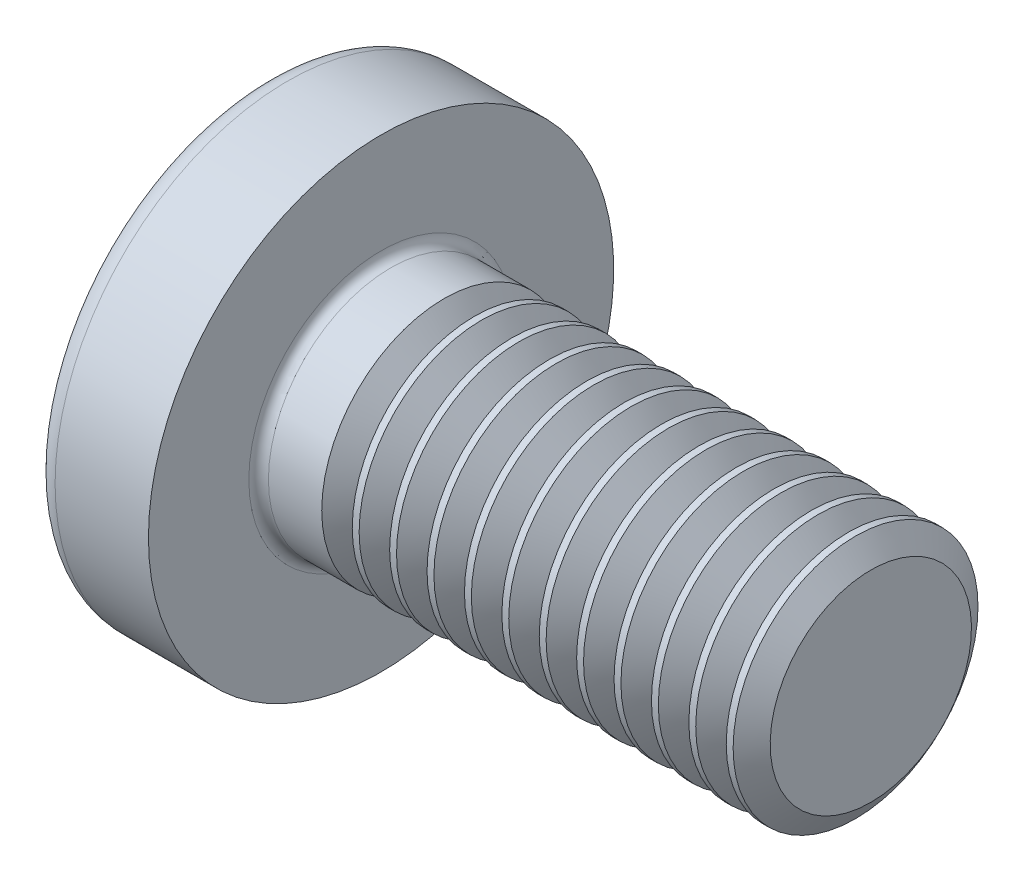
SolidWorks part; units mm, degrees
ref_plane "Plane1" through (0, 0, 0) normal (0, 0, 1) x (1, 0, 0)
ref_plane "Plane2" through (0, 0, 0) normal (0, 1, 0) x (1, 0, 0)
ref_plane "Plane3" through (0, 0, 0) normal (1, 0, 0) x (0, 0, -1)
sketch "BodySke" plane through (0, 0, 0) normal (0, 0, 1) x (1, 0, 0)
  line L0 (3.7, 2.5) -> (3.7, 4.75)
  line L1 (4.1, 6.35) -> (4.1, -3.175) construction
  line L2 (-25.4, 0) -> (127, 0) construction
  line L3 (13.7, 0) -> (0, 0)
  line L4 (3.7, 2.5) -> (13.7, 2.5)
  line L5 (13.7, 2.5) -> (13.7, 0)
  line L6 (1.7942, 4.75) -> (3.7, 4.75)
  line L8 (3.7, 6.35) -> (3.7, -3.175) construction
  arc A0 (1.4243, 4.5563) -> (0, 0) centre (8, 0) ccw
  arc A2 (1.4243, 4.5563) -> (1.7942, 4.75) centre (1.7942, 4.3) cw
  dimension "Head_crown_rad" = 8
  dimension "Head_fillet_rad" = 0.45
  dimension "Length" = 10
  dimension "Head_ht" = 3.7
  dimension "Head_dia" = 9.5
  dimension "Advance" = 0.8
  dimension "Thread_nom" = 10
  dimension "Diameter" = 5
revolve "Base-Revolve" add sketch "BodySke"
cosmetic thread "ThreadCosmetic" [suppressed]
fillet "Fillet1" radius 0.2 1 edges at (3.7, 0, 2.5)
sketch "Sketch3" plane through (0, 0, 0) normal (1, 0, 0) x (0, 0, -1)
  line L0 (0.515, -2.35) -> (-0.515, -2.35)
  line L1 (0.515, -2.35) -> (0.515, 2.35)
  line L2 (-0.515, 2.35) -> (0.515, 2.35)
  line L3 (-0.515, 2.35) -> (-0.515, -2.35)
  dimension "Cross_dia" = 4.7
  dimension "D1" = 2.35
  dimension "Cross_width" = 1.03
  dimension "D2" = 0.515
ref_plane "Plane4" through (2.74, 0, 0) normal (1, 0, 0) x (0, 0, -1)
sketch "Sketch4" plane through (2.74, 0, 0) normal (1, 0, 0) x (0, 0, -1)
  line L0 (0.515, -0.9839) -> (-0.515, -0.9839)
  line L1 (0.515, -0.9839) -> (0.515, 0.9839)
  line L2 (-0.515, 0.9839) -> (0.515, 0.9839)
  line L3 (-0.515, 0.9839) -> (-0.515, -0.9839)
  dimension "D1" = 1.03
  dimension "D2" = 1.9678
  dimension "D3" = 0.515
  dimension "D4" = 0.9839
loft "Recess" cut profiles "Sketch3", "Sketch4"
pattern_circular "RecPat" count 2 every 90 about axis through (0, 0, 0) along (1, 0, 0) of "Recess"
sketch "RecCorSke" plane through (0, 0, 0) normal (0, 0, 1) x (1, 0, 0)
  line L0 (-3.175, 0) -> (15.875, 0) construction
  line L1 (-25.4, 0) -> (127, 0) construction
  line L2 (0, 0) -> (0, 1.0426)
  line L3 (0, 1.0426) -> (2.74, 0.851)
  line L4 (2.74, 0.851) -> (3.0165, 0)
  line L5 (3.0165, 0) -> (0, 0)
  dimension "Diameter" = 1.702
  dimension "Depth" = 2.74
  dimension "Draft_angle" = 4
  dimension "Bottom_angle" = 18
revolve "RecessCore" cut sketch "RecCorSke" angle 360 about L0
sketch "ThdSchSke" plane through (0, 0, 0) normal (0, 0, 1) x (1, 0, 0)
  line L0 (5.3, -2.055) -> (4.9884, -2.5)
  line L1 (5.3, -2.055) -> (5.6116, -2.5)
  line L2 (5.6116, -2.5) -> (5.6116, -3.125)
  line L3 (-3.175, 0) -> (5.1513, 0) construction
  line L5 (5.6116, -3.125) -> (4.9884, -3.125)
  line L6 (4.9884, -3.125) -> (4.9884, -2.5)
  dimension "Diameter" = 5
  dimension "SideAngle" = 55
  dimension "VeeAngle" = 70
  dimension "Thread_minor" = 4.11
  dimension "Overcut" = 6.25
  dimension "Start" = 5.3
revolve "ThreadSchematic" cut sketch "ThdSchSke" angle 360 about L3
pattern_linear "ThdSchPat" count 12 spacing 0.7636 along (1, 0, 0) of "ThreadSchematic"
equation "\"D1@Sketch3\" = \"Cross_dia@Sketch3\" / 2"
equation "\"D2@Sketch3\" = \"Cross_width@Sketch3\" / 2"
equation "\"Depth@RecCorSke\" = \"Cross_depth@Plane4\""
equation "\"D1@Sketch4\" = \"Cross_width@Sketch3\""
equation "\"D2@Sketch4\" = \"Cross_dia@Sketch3\" - 2.0 * \"Cross_depth@Plane4\" * tan(26.5  * 0.017453292)"
equation "\"D3@Sketch4\" = \"D1@Sketch4\" / 2"
equation "\"D4@Sketch4\" = \"D2@Sketch4\" / 2"
equation "\"Thread_length@ThreadCosmetic\" = ((sgn( (\"Length@BodySke\" - \"Advance@BodySke\" * 2.0 ) - \"Thread_nom@BodySke\" )-1)*( (\"Length@BodySke\" - \"Advance@BodySke\" * 2.0 ) - \"Thread_nom@BodySke\" ))/-2+ \"Thread_nom@BodySke\""
equation "\"Thread_minor@ThdSchSke\" = \"Thread_minor@ThreadCosmetic\""
equation "\"Diameter@ThdSchSke\" = \"Diameter@BodySke\""
equation "\"Overcut@ThdSchSke\" = \"Diameter@BodySke\" * 1.25"
equation "\"Start@ThdSchSke\" = \"Head_ht@BodySke\" + \"Length@BodySke\" - \"Thread_length@ThreadCosmetic\"  '---Non-countersunk---"
equation "\"Num_threads@ThdSchPat\" = int( \"Thread_length@ThreadCosmetic\" / \"Advance@BodySke\" + 0.999 )  + 1"
equation "\"Advance@ThdSchPat\" = \"Thread_length@ThreadCosmetic\" /  (\"Num_threads@ThdSchPat\" - 1) 'relax it"
